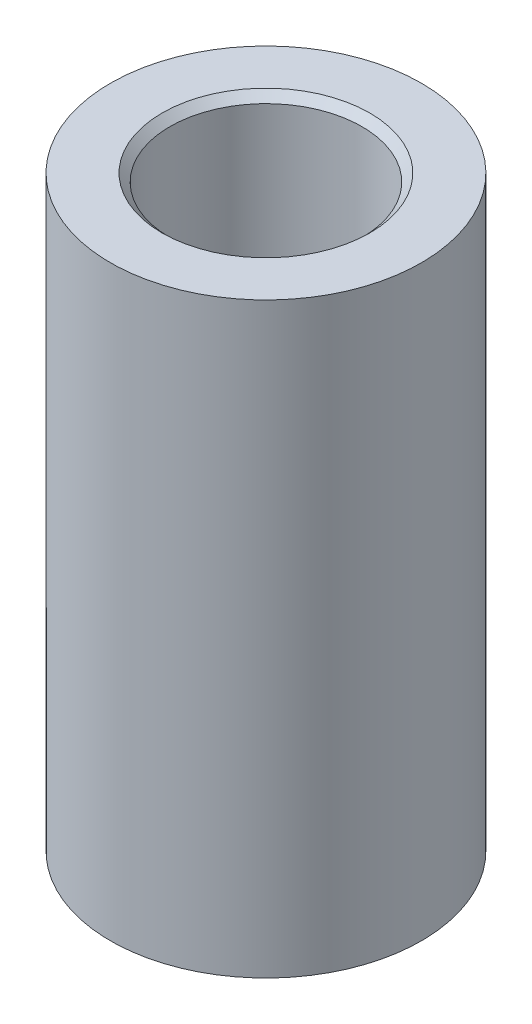
SolidWorks part; units mm, degrees
ref_plane "Front Plane" through (0, 0, 0) normal (0, 0, 1) x (1, 0, 0)
ref_plane "Top Plane" through (0, 0, 0) normal (0, 1, 0) x (1, 0, 0)
ref_plane "Right Plane" through (0, 0, 0) normal (1, 0, 0) x (0, 0, -1)
sketch "Sketch1" plane through (0, 0, 0) normal (0, 1, 0) x (1, 0, 0)
  circle A0 centre (0, 0) radius 7.9375
extrude "Boss-Extrude1" add sketch "Sketch1" along normal blind 29.972
hole_wizard "W (0.386) Diameter Hole1" positions "Sketch3" profile "Sketch4" hole size "W" standard "ANSI Inch" end condition through all
sketch "Sketch3" plane through (0, 29.972, 0) normal (0, 1, 0) x (1, 0, 0)
  point P0 (0, 0)
sketch "Sketch4" plane through (0, 29.972, 0) normal (1, 0, 0) x (0, 0, 1)
  line L0 (0, 0) -> (0, 29.972)
  line L1 (0, 29.972) -> (4.9022, 29.972)
  line L2 (4.9022, 29.972) -> (4.9022, 0)
  line L5 (4.9022, 0) -> (0, 0)
  line L11 (0, -6.35) -> (0, 107.95) construction
  dimension "Thru Hole Dia." = 9.8044
  dimension "Thru Hole Depth" = 29.972
chamfer "Chamfer1" distance 0.4 angle 45 2 edges at (0, 0, 4.9022) (0, 29.972, 4.9022)
